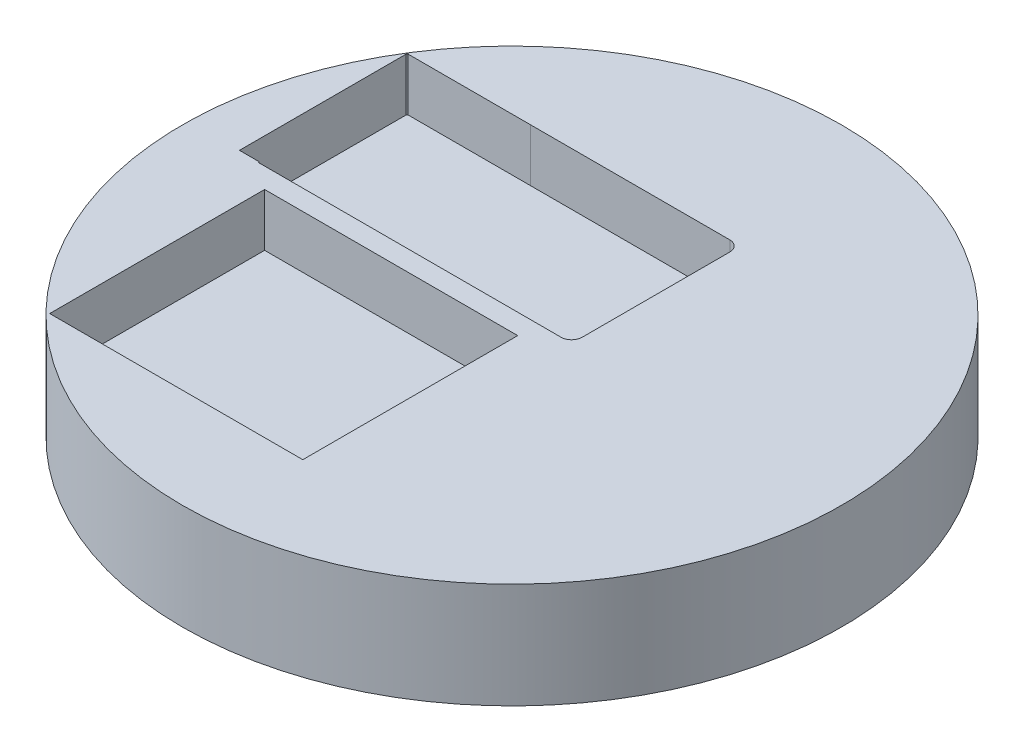
SolidWorks part; units mm, degrees
material "Polyurethane Foam Flexible"
ref_plane "Front Plane" through (0, 0, 0) normal (0, 0, 1) x (1, 0, 0)
ref_plane "Top Plane" through (0, 0, 0) normal (0, 1, 0) x (1, 0, 0)
ref_plane "Right Plane" through (0, 0, 0) normal (1, 0, 0) x (0, 0, -1)
sketch "Sketch1" plane through (0, 0, 0) normal (0, 1, 0) x (1, 0, 0)
  circle A0 centre (0, 0) radius 79.375
  dimension "D1" = 158.75
extrude "Boss-Extrude1" add sketch "Sketch1" along normal blind 25.4
sketch "Sketch2" plane through (0, 25.4, 0) normal (0, 1, 0) x (1, 0, 0)
  line L0 (13.0698, 39.3931) -> (13.0698, 3.8331)
  line L1 (-55.999, -7.4891) -> (-55.999, -8.3781)
  line L2 (-55.999, -7.4891) -> (-55.999, -3.5837)
  line L3 (-55.999, -8.3781) -> (-55.999, -50.5544)
  line L4 (-55.999, -50.5544) -> (-55.999, -51.4434)
  line L5 (-55.999, -55.3489) -> (-55.999, -51.4434)
  line L6 (-55.999, -55.3489) -> (4.961, -55.3489)
  line L7 (4.961, -51.4434) -> (4.961, -55.3489)
  line L8 (4.961, -51.4434) -> (4.961, -50.5544)
  line L9 (4.961, -8.3781) -> (4.961, -7.4891)
  line L10 (4.961, -50.5544) -> (4.961, -8.3781)
  line L11 (4.961, -3.5837) -> (4.961, -7.4891)
  line L12 (4.961, -3.5837) -> (-55.999, -3.5837)
  line L13 (-67.1939, 16.2029) -> (-67.1939, 1.5471)
  line L14 (-67.1939, 1.5471) -> (-62.427, 1.5471)
  line L15 (-37.4759, 1.2931) -> (-62.3666, 1.2931)
  line L16 (10.5298, 1.2931) -> (-37.2219, 1.2931)
  line L17 (-37.2219, 41.9331) -> (10.5298, 41.9331)
  line L18 (-62.3666, 41.9331) -> (-37.4759, 41.9331)
  line L19 (-62.3666, 41.9331) -> (-66.9399, 41.9331)
  line L20 (-67.1939, 41.6791) -> (-67.1939, 27.0234)
  line L21 (-67.1939, 27.0234) -> (-67.1939, 16.2029)
  line L22 (-62.427, 1.5471) -> (-62.3666, 1.2931)
  line L23 (-37.4759, 1.2931) -> (-37.2219, 1.2931)
  line L24 (-37.4759, 41.9331) -> (-37.2219, 41.9331)
  line L25 (-67.1939, 41.6791) -> (-66.9399, 41.9331)
  arc A0 (10.5298, 1.2931) -> (13.0698, 3.8331) centre (10.5298, 3.8331) ccw
  arc A1 (13.0698, 39.3931) -> (10.5298, 41.9331) centre (10.5298, 39.3931) ccw
extrude "Cut-Extrude1" cut sketch "Sketch2" against normal blind 12.7 contours L11 L12 L2 L1 L3 L4 L5 L6 L7 L8 L10 L9 | L0 A1 L17 L24 L18 L19 L25 L20 L21 L13 L14 L22 L15 L23 L16 A0
